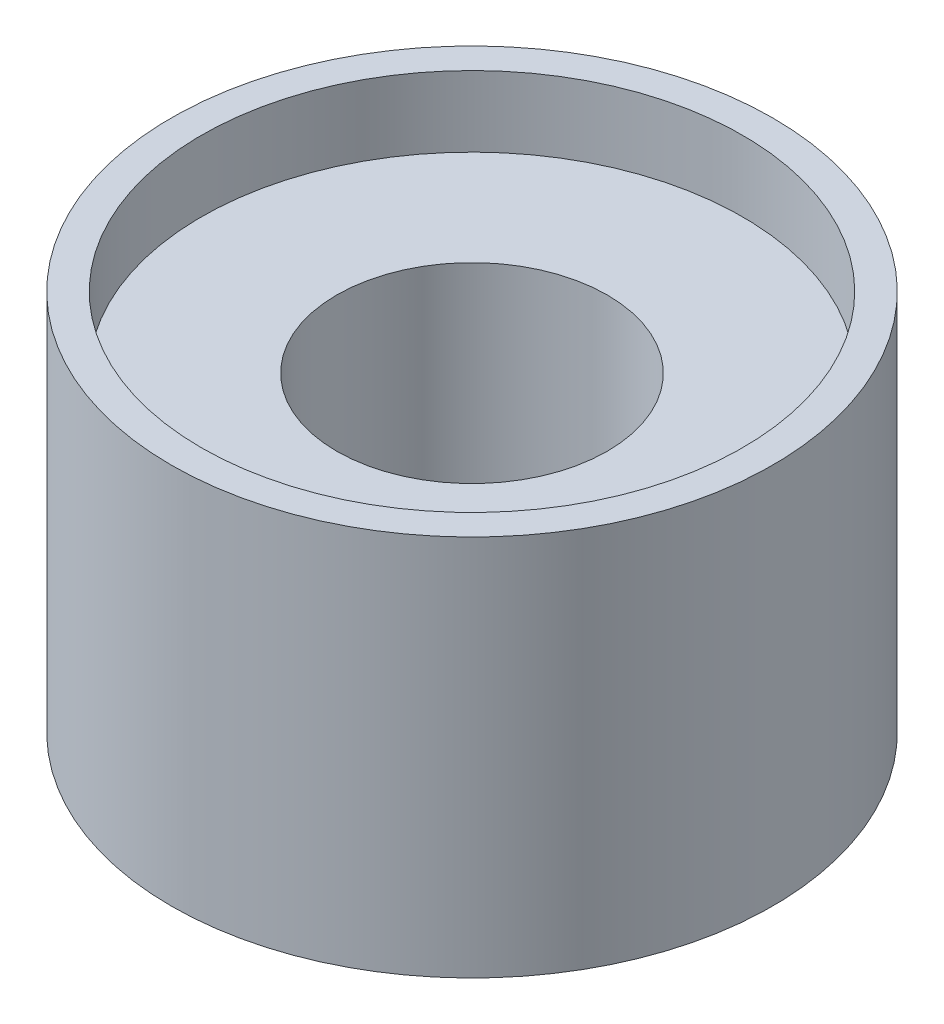
SolidWorks part; units mm, degrees
ref_plane "Front" through (0, 0, 0) normal (0, 0, 1) x (1, 0, 0)
ref_plane "Top" through (0, 0, 0) normal (0, 1, 0) x (1, 0, 0)
ref_plane "Right" through (0, 0, 0) normal (1, 0, 0) x (0, 0, -1)
sketch "Sketch1" plane through (0, 0, 0) normal (0, 1, 0) x (1, 0, 0)
  circle A0 centre (0, 0) radius 100
  circle A1 centre (0, 0) radius 90
  dimension "D1" = 180
  dimension "D2" = 200
extrude "Boss-Extrude1" add sketch "Sketch1" along normal mid plane 127
sketch "Sketch4" plane through (0, 0, 0) normal (0, 1, 0) x (1, 0, 0)
  circle A0 centre (0, 0) radius 90
  circle A1 centre (0, 0) radius 45
  dimension "D1" = 180
  dimension "D2" = 90
extrude "Boss-Extrude2" add sketch "Sketch4" along normal mid plane 80
